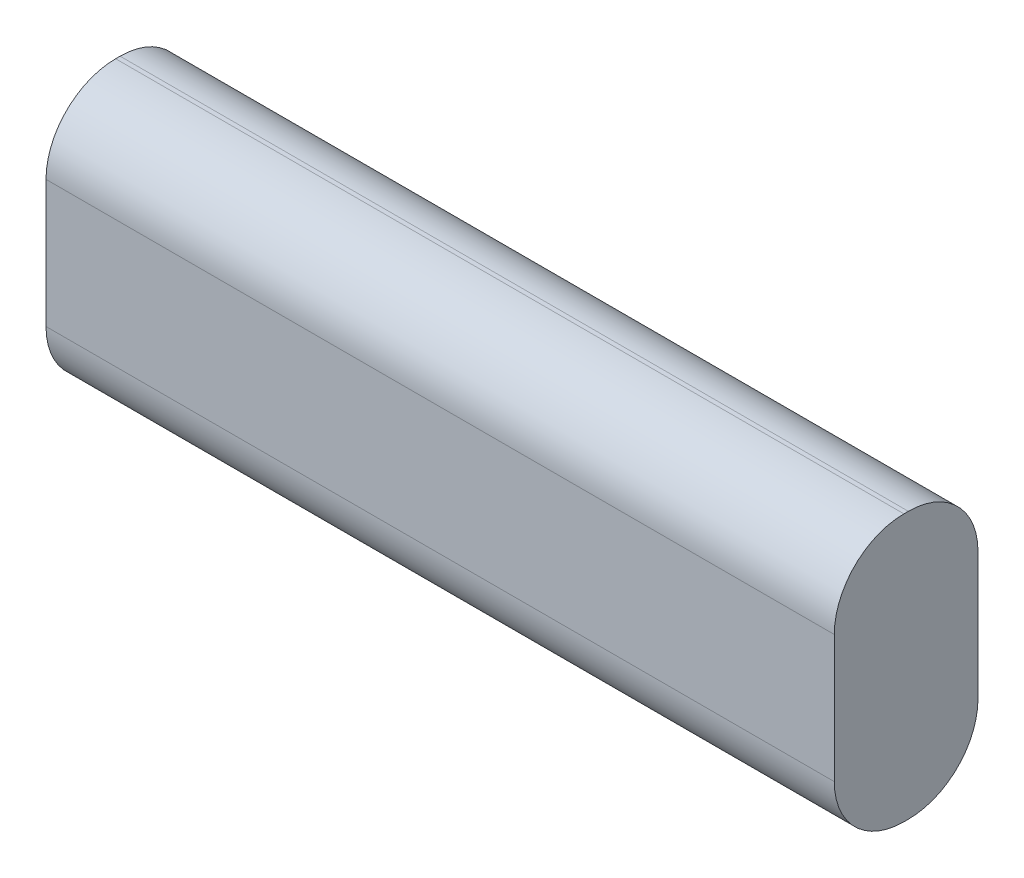
SolidWorks part; units mm, degrees
ref_plane "Front Plane" through (0, 0, 0) normal (0, 0, 1) x (1, 0, 0)
ref_plane "Top Plane" through (0, 0, 0) normal (0, 1, 0) x (1, 0, 0)
ref_plane "Right Plane" through (0, 0, 0) normal (1, 0, 0) x (0, 0, -1)
sketch "Sketch1" plane through (0, 0, 0) normal (0, 0, 1) x (1, 0, 0)
  line L1 (0, 0) -> (133, 0)
  line L2 (0, 0) -> (0, -45)
  line L3 (0, -45) -> (133, -45)
  line L4 (133, 0) -> (133, -45)
  dimension "D1" = 133
  dimension "D2" = 45
extrude "Boss-Extrude1" add sketch "Sketch1" along normal blind 24.25
fillet "Fillet1" radius 11.75 4 edges at (66.5, -45, 0) (66.5, -45, 24.25) (66.5, 0, 24.25) (66.5, 0, 0)
